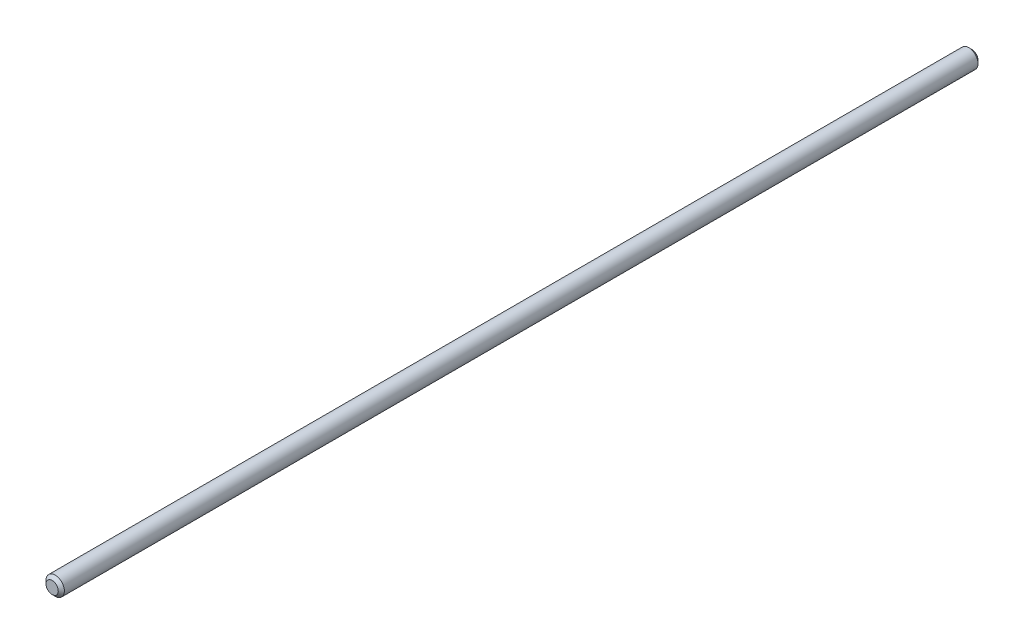
SolidWorks part; units mm, degrees
ref_plane "Ön Düzlem" through (0, 0, 0) normal (0, 0, 1) x (1, 0, 0)
ref_plane "Üst Düzlem" through (0, 0, 0) normal (0, 1, 0) x (1, 0, 0)
ref_plane "Sağ Düzlem" through (0, 0, 0) normal (1, 0, 0) x (0, 0, -1)
sketch "Sketch1" plane through (0, 0, 0) normal (0, 0, 1) x (1, 0, 0)
  circle A0 centre (0, 0) radius 6
  dimension "12" = 12
extrude "Boss-Extrude1" add sketch "Sketch1" along normal blind 600
chamfer "Chamfer1" distance 2 angle 45 2 edges at (6, 0, 0) (6, 0, 600)
